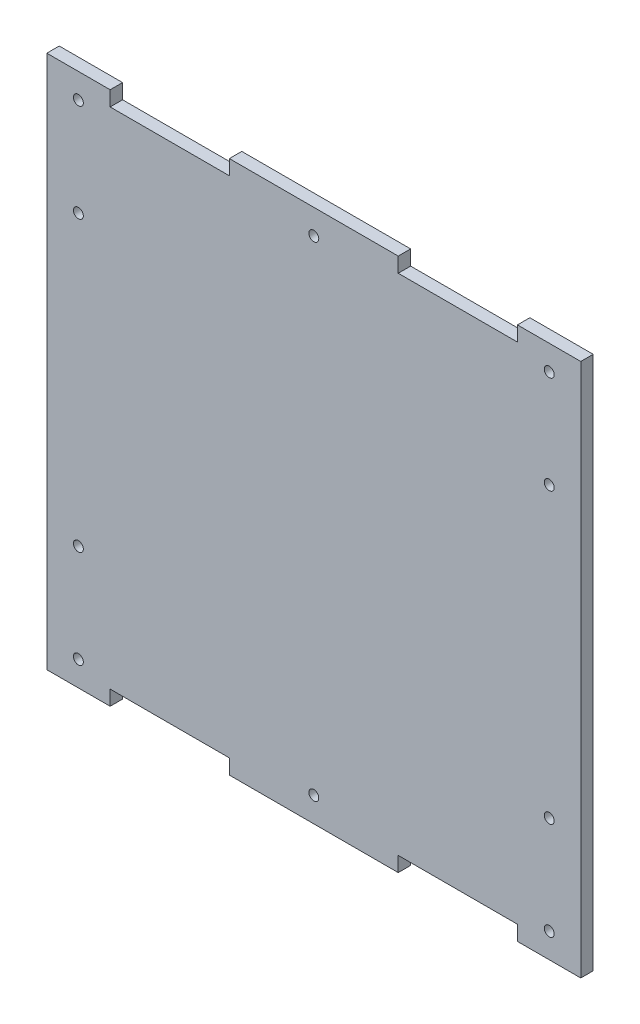
SolidWorks part; units mm, degrees
material "ABS PC"
ref_plane "Front Plane" through (0, 0, 0) normal (0, 0, 1) x (1, 0, 0)
ref_plane "Top Plane" through (0, 0, 0) normal (0, 1, 0) x (1, 0, 0)
ref_plane "Right Plane" through (0, 0, 0) normal (1, 0, 0) x (0, 0, -1)
sketch "Sketch2" plane through (0, 0, 0) normal (0, 0, 1) x (1, 0, 0)
  line L0 (-148.1492, 0) -> (167.2874, 0) construction
  line L1 (-136.525, -136.525) -> (136.525, -136.525)
  line L2 (-136.525, -136.525) -> (-136.525, 136.525)
  line L3 (-136.525, 136.525) -> (136.525, 136.525)
  line L4 (136.525, -136.525) -> (136.525, 136.525)
  line L5 (-136.525, -136.525) -> (136.525, 136.525) construction
  line L6 (-136.525, 136.525) -> (136.525, -136.525) construction
  line L7 (0, 204.6077) -> (0, -224.7364) construction
  circle A0 centre (-120.396, 123.825) radius 2.54
  circle A1 centre (-120.396, 73.787) radius 2.54
  circle A2 centre (0, 123.825) radius 2.54
  circle A3 centre (120.396, 73.787) radius 2.54
  circle A4 centre (120.396, 123.825) radius 2.54
  circle A5 centre (120.396, -123.825) radius 2.54
  circle A6 centre (120.396, -73.787) radius 2.54
  circle A7 centre (0, -123.825) radius 2.54
  circle A8 centre (-120.396, -73.787) radius 2.54
  circle A9 centre (-120.396, -123.825) radius 2.54
  point P0 (0, 0)
  dimension "D4" = 5.08
  dimension "D7" = 5.08
  dimension "D8" = 5.08
  dimension "D1" = 273.05
  dimension "D2" = 273.05
  dimension "D3" = 120.396
  dimension "D5" = 123.825
  dimension "D6" = 50.038
extrude "Boss-Extrude1" add sketch "Sketch2" along normal blind 6.35
sketch "Sketch3" plane through (0, 0, 6.35) normal (0, 0, 1) x (1, 0, 0)
  line L0 (0, 160.7885) -> (0, -171.3941) construction
  line L1 (-158.7053, 0) -> (205.6729, 0) construction
  line L4 (136.525, 136.525) -> (-136.525, 136.525) construction
  line L5 (104.14, 128.905) -> (43.18, 128.905)
  line L6 (104.14, 146.1851) -> (43.18, 146.1851)
  line L7 (-104.14, 146.1851) -> (-104.14, 128.905)
  line L8 (43.18, 128.905) -> (43.18, 146.1851)
  line L9 (104.14, 146.1851) -> (104.14, 128.905)
  line L10 (-104.14, -128.905) -> (-43.18, -128.905)
  line L11 (-43.18, 128.905) -> (-43.18, 146.1851)
  line L12 (-104.14, -146.1851) -> (-43.18, -146.1851)
  line L13 (-104.14, 146.1851) -> (-43.18, 146.1851)
  line L14 (-104.14, 128.905) -> (-43.18, 128.905)
  line L15 (-43.18, -128.905) -> (-43.18, -146.1851)
  line L16 (104.14, -146.1851) -> (104.14, -128.905)
  line L17 (43.18, -128.905) -> (43.18, -146.1851)
  line L18 (-104.14, -146.1851) -> (-104.14, -128.905)
  line L19 (104.14, -146.1851) -> (43.18, -146.1851)
  line L20 (104.14, -128.905) -> (43.18, -128.905)
  dimension "D1" = 7.62
  dimension "D2" = 43.18
  dimension "D3" = 104.14
extrude "Cut-Extrude1" cut sketch "Sketch3" against normal through all
